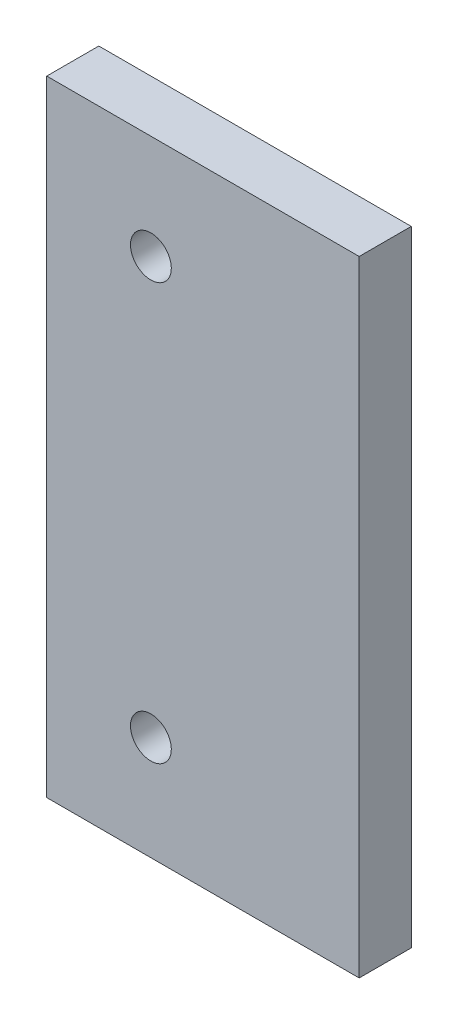
SolidWorks part; units mm, degrees
material "6061 Alloy"
ref_plane "X-Y Datum" through (0, 0, 0) normal (0, 0, 1) x (1, 0, 0)
ref_plane "X-Z Datum" through (0, 0, 0) normal (0, 1, 0) x (1, 0, 0)
ref_plane "Y-Z Datum" through (0, 0, 0) normal (1, 0, 0) x (0, 0, -1)
sketch "Sketch2" plane through (0, 0, 0) normal (0, 0, 1) x (1, 0, 0)
  line L1 (-19.05, -38.1) -> (19.05, -38.1)
  line L2 (-19.05, -38.1) -> (-19.05, 38.1)
  line L3 (-19.05, 38.1) -> (19.05, 38.1)
  line L4 (19.05, -38.1) -> (19.05, 38.1)
  circle A0 centre (-6.35, 25.4) radius 2.4892
  circle A1 centre (-6.35, -25.4) radius 2.4892
  point P4 (-19.05, 0)
  point P6 (0, 38.1)
  dimension "D3" = 4.9784
  dimension "D6" = 12.7
  dimension "D1" = 38.1
  dimension "D2" = 76.2
  dimension "D4" = 12.7
  dimension "D5" = 12.7
extrude "Boss-Extrude1" add sketch "Sketch2" along normal mid plane 6.35
